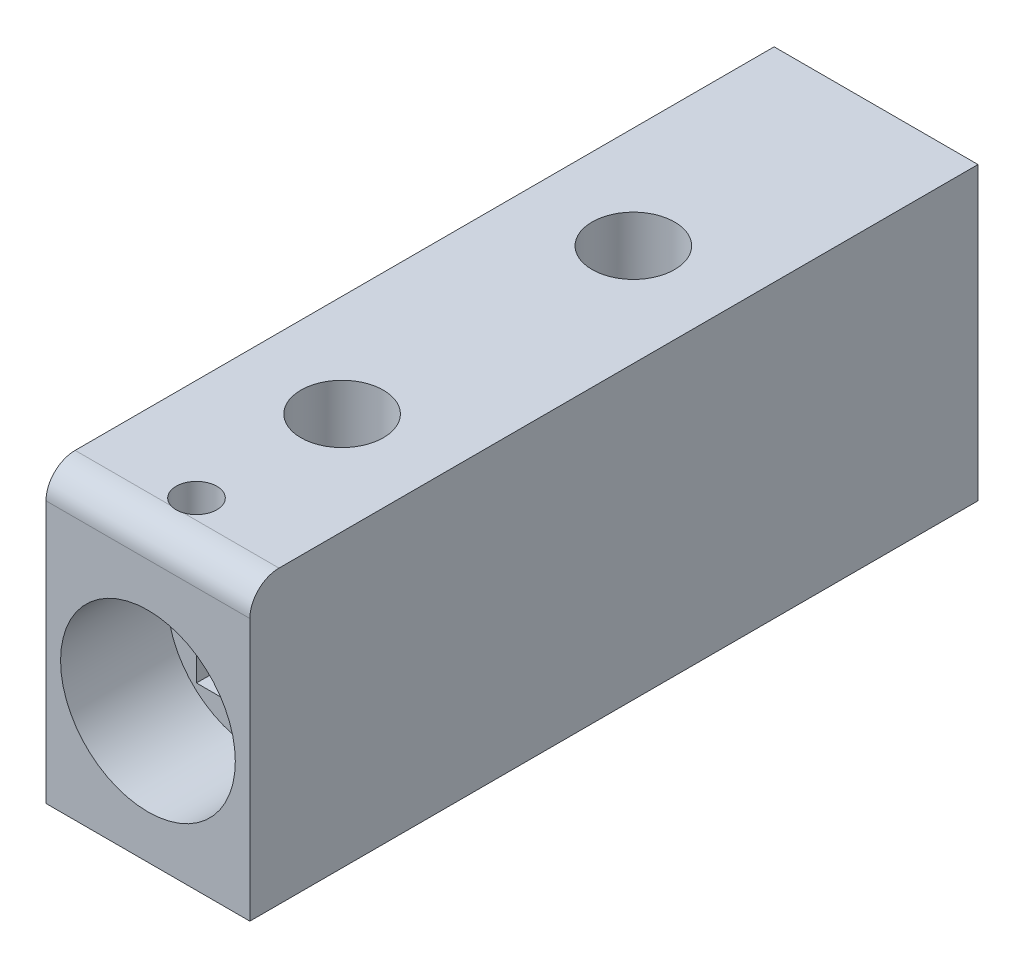
SolidWorks part; units mm, degrees
ref_plane "前视基准面" through (0, 0, 0) normal (0, 0, 1) x (1, 0, 0)
ref_plane "上视基准面" through (0, 0, 0) normal (0, 1, 0) x (1, 0, 0)
ref_plane "右视基准面" through (0, 0, 0) normal (1, 0, 0) x (0, 0, -1)
sketch "草图1" plane through (0, 0, 0) normal (0, 0, 1) x (1, 0, 0)
  line L0 (0, -55) -> (0, 55) construction
  line L1 (-10.5, 30) -> (10.5, 30)
  line L2 (-10.5, 30) -> (-10.5, 0)
  line L3 (-10.5, 0) -> (10.5, 0)
  line L4 (10.5, 30) -> (10.5, 0)
  line L5 (-10.5, 30) -> (10.5, 0) construction
  line L6 (-10.5, 0) -> (10.5, 30) construction
  line L7 (55, 0) -> (-55, 0) construction
  point P0 (0, 15)
  dimension "D1" = 30
  dimension "D2" = 21
extrude "凸台-拉伸1" add sketch "草图1" against normal blind 75
sketch "草图2" plane through (0, 0, 0) normal (0, 0, 1) x (1, 0, 0)
  line L0 (0, -16.5) -> (0, 16.5) construction
  line L1 (11.55, 0) -> (-11.55, 0) construction
  circle A0 centre (0, 13.5) radius 9
  dimension "D1" = 18
  dimension "D2" = 13.5
extrude "切除-拉伸1" cut sketch "草图2" against normal blind 11 and the other way through all
sketch "草图3" plane through (0, 0, -11) normal (0, 0, 1) x (1, 0, 0)
  line L1 (-6, 7.5) -> (6, 7.5)
  line L2 (-6, 7.5) -> (-6, 19.5)
  line L3 (-6, 19.5) -> (6, 19.5)
  line L4 (6, 7.5) -> (6, 19.5)
  line L5 (-6, 7.5) -> (6, 19.5) construction
  line L6 (-6, 19.5) -> (6, 7.5) construction
  point P0 (0, 13.5)
  dimension "D1" = 12
extrude "切除-拉伸2" cut sketch "草图3" against normal through all
fillet "圆角1" radius 3 1 edges at (0, 30, 0)
hole_wizard "M5 螺纹孔1" positions "草图5" profile "草图6" tap size "M5" standard "GB"
sketch "草图5" plane through (0, 30, 0) normal (0, 1, 0) x (1, 0, 0)
  line L0 (0, -16.5) -> (0, 16.5) construction
  line L1 (-11.55, 0) -> (11.55, 0) construction
  point P0 (0, 5)
  dimension "D1" = 5
sketch "草图6" plane through (0, 30, -5) normal (1, 0, 0) x (0, 0, 1)
  line L0 (0, 0) -> (0, 7.5)
  line L1 (0, 7.5) -> (2.1, 7.5)
  line L2 (2.1, 7.5) -> (2.1, 0)
  line L5 (2.1, 0) -> (0, 0)
  line L11 (0, -6.35) -> (0, 107.95) construction
  dimension "通孔螺纹孔钻头直径" = 4.2
  dimension "通孔螺纹孔钻头深度" = 7.5
cosmetic thread "孔螺纹线1" parameters "D2"=5
hole_wizard "M10 螺纹孔1" positions "草图7" profile "草图8" tap size "M10" standard "GB"
sketch "草图7" plane through (0, 30, 0) normal (0, 1, 0) x (1, 0, 0)
  line L0 (0, -16.5) -> (0, 16.5) construction
  line L2 (-11.55, 0) -> (11.55, 0) construction
  point P0 (0, 20)
  point P4 (0, 50)
  point P11 (23.4033, 9.9977)
  dimension "D1" = 30
  dimension "D2" = 20
sketch "草图8" plane through (0, 30, -20) normal (1, 0, 0) x (0, 0, 1)
  line L0 (0, 0) -> (0, 10.5)
  line L1 (0, 10.5) -> (4.25, 10.5)
  line L2 (4.25, 10.5) -> (4.25, 0)
  line L5 (4.25, 0) -> (0, 0)
  line L11 (0, -6.35) -> (0, 107.95) construction
  dimension "通孔螺纹孔钻头直径" = 8.5
  dimension "通孔螺纹孔钻头深度" = 10.5
cosmetic thread "孔螺纹线2" parameters "D2"=10
cosmetic thread "孔螺纹线3" parameters "D2"=10
